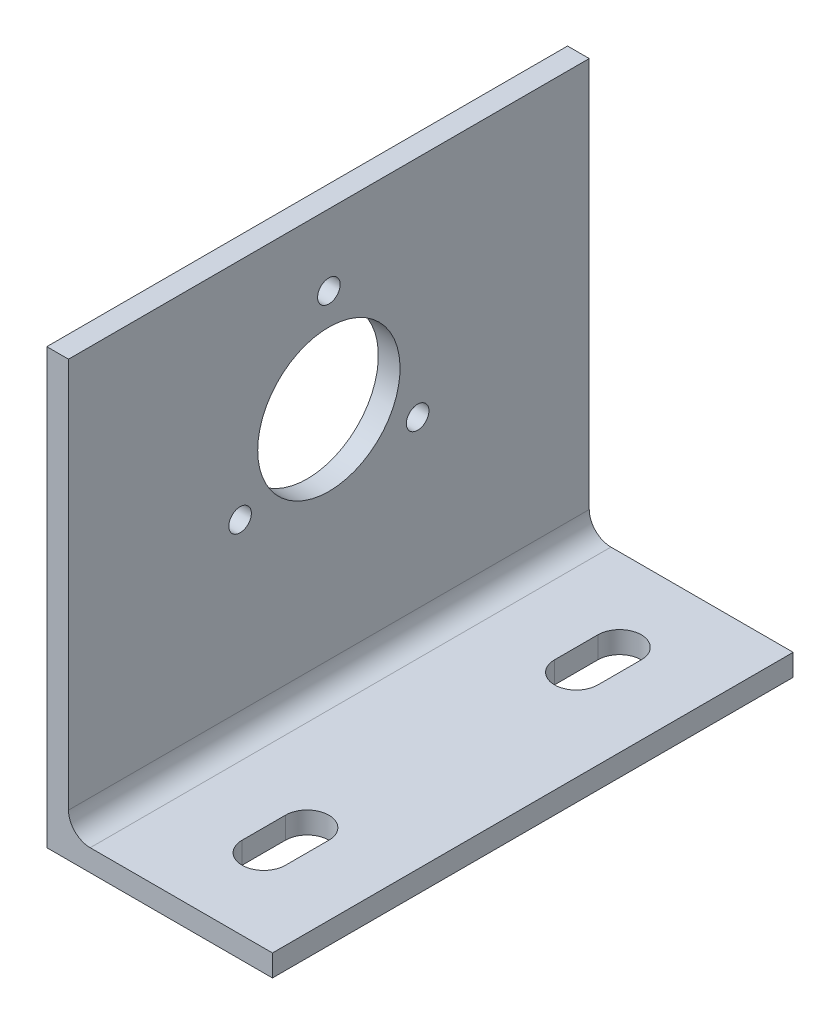
SolidWorks part; units mm, degrees
ref_plane "Front Plane" through (0, 0, 0) normal (0, 0, 1) x (1, 0, 0)
ref_plane "Top Plane" through (0, 0, 0) normal (0, 1, 0) x (1, 0, 0)
ref_plane "Right Plane" through (0, 0, 0) normal (1, 0, 0) x (0, 0, -1)
sketch "Sketch1" plane through (0, 0, 0) normal (0, 0, 1) x (1, 0, 0)
  line L0 (0, 0) -> (0, 63.5)
  line L1 (0, 63.5) -> (3.175, 63.5)
  line L2 (3.175, 63.5) -> (3.175, 3.175)
  line L3 (3.175, 3.175) -> (101.6, 3.175)
  line L4 (101.6, 3.175) -> (101.6, 0)
  line L5 (101.6, 0) -> (0, 0)
  dimension "D1" = 63.5
  dimension "D2" = 101.6
  dimension "D3" = 3.175
  dimension "D4" = 3.175
extrude "Boss-Extrude1" add sketch "Sketch1" along normal blind 76.2
fillet "Fillet1" radius 3.175 1 edges at (3.175, 3.175, 38.1)
sketch "Sketch2" plane through (0, 0, 0) normal (-1, 0, 0) x (0, 0, 1)
  line L0 (76.2, 0) -> (0, 0) construction
  line L1 (0, 63.5) -> (0, 0) construction
  circle A0 centre (38.1, 38.1) radius 10.414
  circle A1 centre (38.1, 53.1) radius 1.651
  circle A4 centre (38.1, 38.1) radius 10.414
  circle A5 centre (51.0904, 30.6) radius 1.651
  circle A6 centre (38.1, 38.1) radius 10.414
  circle A7 centre (25.1096, 30.6) radius 1.651
  point P15 (25.4, 38.1)
  point P17 (38.1, 38.1)
  dimension "D2" = 20.828
  dimension "D4" = 3.302
  dimension "D1" = 38.1
  dimension "D3" = 38.1
  dimension "D5" = 15
  dimension "D6" = 3
extrude "Cut-Extrude2" cut sketch "Sketch2" against normal through all contours A0 | A1 | A7 | A5
sketch "Sketch4" plane through (0, 3.175, 0) normal (0, 1, 0) x (1, 0, 0)
  line L0 (101.6, -76.2) -> (6.35, -76.2) construction
  line L1 (101.6, 0) -> (33.02, 0)
  line L2 (101.6, 0) -> (101.6, -76.2)
  line L3 (101.6, -76.2) -> (33.02, -76.2)
  line L4 (33.02, 0) -> (33.02, -76.2)
  dimension "D1" = 68.58
extrude "Cut-Extrude3" cut sketch "Sketch4" against normal through all
sketch "Sketch5" plane through (0, 3.175, 0) normal (0, 1, 0) x (1, 0, 0)
  line L0 (19.685, 0) -> (19.685, -76.2) construction
  line L1 (33.02, 0) -> (6.35, 0) construction
  line L2 (33.02, -76.2) -> (6.35, -76.2) construction
  line L3 (33.02, 0) -> (33.02, -76.2) construction
  line L4 (19.685, -12.065) -> (19.685, -18.415) construction
  line L5 (22.86, -12.065) -> (22.86, -18.415)
  line L6 (16.51, -12.065) -> (16.51, -18.415)
  line L7 (19.685, -38.1) -> (12.703, -38.1) construction
  line L8 (19.685, -64.135) -> (19.685, -57.785) construction
  line L9 (22.86, -64.135) -> (22.86, -57.785)
  line L10 (16.51, -64.135) -> (16.51, -57.785)
  arc A0 (22.86, -12.065) -> (16.51, -12.065) centre (19.685, -12.065) ccw
  arc A1 (16.51, -18.415) -> (22.86, -18.415) centre (19.685, -18.415) ccw
  arc A2 (22.86, -64.135) -> (16.51, -64.135) centre (19.685, -64.135) cw
  arc A3 (16.51, -57.785) -> (22.86, -57.785) centre (19.685, -57.785) cw
  point P10 (19.685, -15.24)
  point P19 (19.685, -60.96)
  dimension "D1" = 13.335
  dimension "D2" = 6.35
  dimension "D3" = 6.35
  dimension "D4" = 15.24
extrude "Cut-Extrude4" cut sketch "Sketch5" against normal through all
